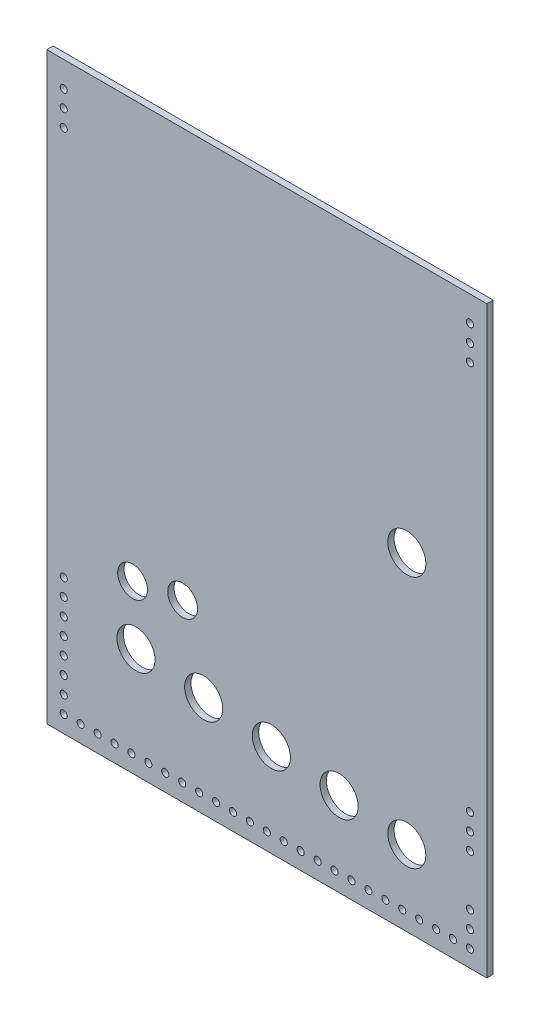
SolidWorks part; units mm, degrees
material "Polypropylene"
ref_plane "Front Plane" through (0, 0, 0) normal (0, 0, 1) x (1, 0, 0)
ref_plane "Top Plane" through (0, 0, 0) normal (0, 1, 0) x (1, 0, 0)
ref_plane "Right Plane" through (0, 0, 0) normal (1, 0, 0) x (0, 0, -1)
sketch "Sketch1" plane through (0, 0, 0) normal (0, 0, 1) x (1, 0, 0)
  line L0 (270.1144, -382.3444) -> (270.1144, -191.8444) construction
  line L1 (0, 0) -> (330.2, 0)
  line L2 (0, 0) -> (0, -438.15)
  line L3 (0, -438.15) -> (330.2, -438.15)
  line L4 (330.2, 0) -> (330.2, -438.15)
  circle A4 centre (270.1144, -191.8444) radius 14.2875
  circle A5 centre (101.9257, -306.8134) radius 11.176
  circle A6 centre (64.3744, -313.2564) radius 11.176
  dimension "D4" = 28.575
  dimension "D5" = 22.352
  dimension "D6" = 22.352
  dimension "D1" = 438.15
  dimension "D2" = 330.2
  dimension "D3" = 190.5
extrude "Boss-Extrude1" add sketch "Sketch1" along normal blind 4.7625
sketch "Sketch2" plane through (0, 0, 4.7625) normal (0, 0, 1) x (1, 0, 0)
  circle A1 centre (66.9144, -355.9045) radius 14.2875
  dimension "D1" = 28.575
extrude "Cut-Extrude1" cut sketch "Sketch2" against normal up to surface (4.7625 mm away) up to face at (165.1, -219.075, 0)
sketch "Sketch3" plane through (0, 0, 4.7625) normal (0, 0, 1) x (1, 0, 0)
  line L0 (66.9144, -355.9045) -> (330.2, -355.9045) construction
  line L1 (330.2, -438.15) -> (330.2, 0) construction
  line L2 (66.9144, -355.9045) -> (117.7144, -355.9045) construction
  line L3 (117.7144, -355.9045) -> (168.5144, -355.9045) construction
  line L4 (168.5144, -355.9045) -> (219.3144, -355.9045) construction
  line L5 (219.3144, -355.9045) -> (270.1144, -355.9045) construction
  line L6 (117.7144, -355.9045) -> (117.7144, -362.2545) construction
  line L7 (168.5144, -355.9045) -> (168.5144, -368.6045) construction
  line L8 (219.3144, -355.9045) -> (219.3144, -374.9545) construction
  line L9 (270.1144, -355.9045) -> (270.1144, -381.3045) construction
  line L10 (117.7144, -355.9045) -> (117.7144, -362.2545) construction
  circle A0 centre (117.7144, -362.2545) radius 14.2875
  circle A1 centre (168.5144, -368.6045) radius 14.2875
  circle A2 centre (219.3144, -374.9545) radius 14.2875
  circle A3 centre (270.1144, -381.3045) radius 14.2875
  dimension "D8" = 28.575
  dimension "D9" = 28.575
  dimension "D10" = 28.575
  dimension "D11" = 28.575
  dimension "D1" = 50.8
  dimension "D2" = 50.8
  dimension "D3" = 50.8
  dimension "D4" = 50.8
  dimension "D5" = 12.7
  dimension "D6" = 19.05
  dimension "D7" = 25.4
  dimension "D12" = 6.35
extrude "Cut-Extrude2" cut sketch "Sketch3" against normal up to surface (4.7625 mm away) contours A0 | A1 | A2 | A3 up to face at (81.2019, -355.9045, 0)
sketch "Sketch4" plane through (0, 0, 0) normal (0, 0, -1) x (-1, 0, 0)
  line L0 (-12.7, -438.15) -> (-12.7, -425.45) construction
  line L1 (0, -438.15) -> (-330.2, -438.15) construction
  line L2 (-12.7, -425.45) -> (0, -425.45) construction
  line L3 (0, 0) -> (0, -438.15) construction
  line L4 (-330.2, -425.45) -> (0, -425.45) construction
  line L5 (-330.2, 0) -> (0, 0) construction
  line L6 (-165.1, 0) -> (-165.1, -438.15) construction
  line L7 (-330.2, -438.15) -> (-330.2, 0) construction
  line L8 (-317.5, -438.15) -> (-317.5, -425.45) construction
  circle A0 centre (-12.7, -425.45) radius 2.667
  circle A1 centre (-12.7, -412.75) radius 2.667
  circle A2 centre (-12.7, -400.05) radius 2.667
  circle A3 centre (-12.7, -387.35) radius 2.667
  circle A4 centre (-12.7, -374.65) radius 2.667
  circle A5 centre (-12.7, -361.95) radius 2.667
  circle A6 centre (-12.7, -349.25) radius 2.667
  circle A7 centre (-12.7, -336.55) radius 2.667
  circle A30 centre (-12.7, -44.45) radius 2.667
  circle A31 centre (-12.7, -31.75) radius 2.667
  circle A32 centre (-12.7, -19.05) radius 2.667
  circle A33 centre (-317.5, -361.95) radius 2.667
  circle A34 centre (-317.5, -349.25) radius 2.667
  circle A35 centre (-317.5, -336.55) radius 2.667
  circle A38 centre (-317.5, -400.05) radius 2.667
  circle A39 centre (-317.5, -412.75) radius 2.667
  circle A40 centre (-317.5, -425.45) radius 2.667
  circle A41 centre (-317.5, -44.45) radius 2.667
  circle A42 centre (-317.5, -31.75) radius 2.667
  circle A43 centre (-317.5, -19.05) radius 2.667
  circle A44 centre (-12.7, -57.15) radius 2.667 [skipped]
  circle A45 centre (-12.7, -69.85) radius 2.667 [skipped]
  circle A46 centre (-12.7, -82.55) radius 2.667 [skipped]
  circle A47 centre (-12.7, -95.25) radius 2.667 [skipped]
  circle A48 centre (-12.7, -107.95) radius 2.667 [skipped]
  circle A49 centre (-12.7, -120.65) radius 2.667 [skipped]
  circle A50 centre (-12.7, -133.35) radius 2.667 [skipped]
  circle A51 centre (-12.7, -146.05) radius 2.667 [skipped]
  circle A52 centre (-12.7, -184.15) radius 2.667 [skipped]
  circle A53 centre (-12.7, -171.45) radius 2.667 [skipped]
  circle A54 centre (-12.7, -158.75) radius 2.667 [skipped]
  circle A55 centre (-12.7, -285.75) radius 2.667 [skipped]
  circle A56 centre (-12.7, -273.05) radius 2.667 [skipped]
  circle A57 centre (-12.7, -260.35) radius 2.667 [skipped]
  circle A58 centre (-12.7, -247.65) radius 2.667 [skipped]
  circle A59 centre (-12.7, -234.95) radius 2.667 [skipped]
  circle A60 centre (-12.7, -222.25) radius 2.667 [skipped]
  circle A61 centre (-12.7, -209.55) radius 2.667 [skipped]
  circle A62 centre (-12.7, -196.85) radius 2.667 [skipped]
  circle A63 centre (-12.7, -323.85) radius 2.667 [skipped]
  circle A64 centre (-12.7, -311.15) radius 2.667 [skipped]
  circle A65 centre (-12.7, -298.45) radius 2.667 [skipped]
  circle A66 centre (-25.4, -425.45) radius 2.667
  circle A67 centre (-38.1, -425.45) radius 2.667
  circle A68 centre (-50.8, -425.45) radius 2.667
  circle A69 centre (-63.5, -425.45) radius 2.667
  circle A70 centre (-76.2, -425.45) radius 2.667
  circle A71 centre (-88.9, -425.45) radius 2.667
  circle A72 centre (-101.6, -425.45) radius 2.667
  circle A73 centre (-114.3, -425.45) radius 2.667
  circle A74 centre (-127, -425.45) radius 2.667
  circle A75 centre (-139.7, -425.45) radius 2.667
  circle A76 centre (-152.4, -425.45) radius 2.667
  circle A77 centre (-165.1, -425.45) radius 2.667
  circle A78 centre (-177.8, -425.45) radius 2.667
  circle A79 centre (-190.5, -425.45) radius 2.667
  circle A80 centre (-203.2, -425.45) radius 2.667
  circle A81 centre (-215.9, -425.45) radius 2.667
  circle A82 centre (-228.6, -425.45) radius 2.667
  circle A83 centre (-241.3, -425.45) radius 2.667
  circle A84 centre (-254, -425.45) radius 2.667
  circle A85 centre (-266.7, -425.45) radius 2.667
  circle A86 centre (-279.4, -425.45) radius 2.667
  circle A87 centre (-292.1, -425.45) radius 2.667
  circle A88 centre (-304.8, -425.45) radius 2.667
  dimension "D3" = 5.334
  dimension "D1" = 12.7
  dimension "D2" = 12.7
  dimension "D4" = 24
  dimension "D5" = 33
extrude "Cut-Extrude3" cut sketch "Sketch4" against normal through all
